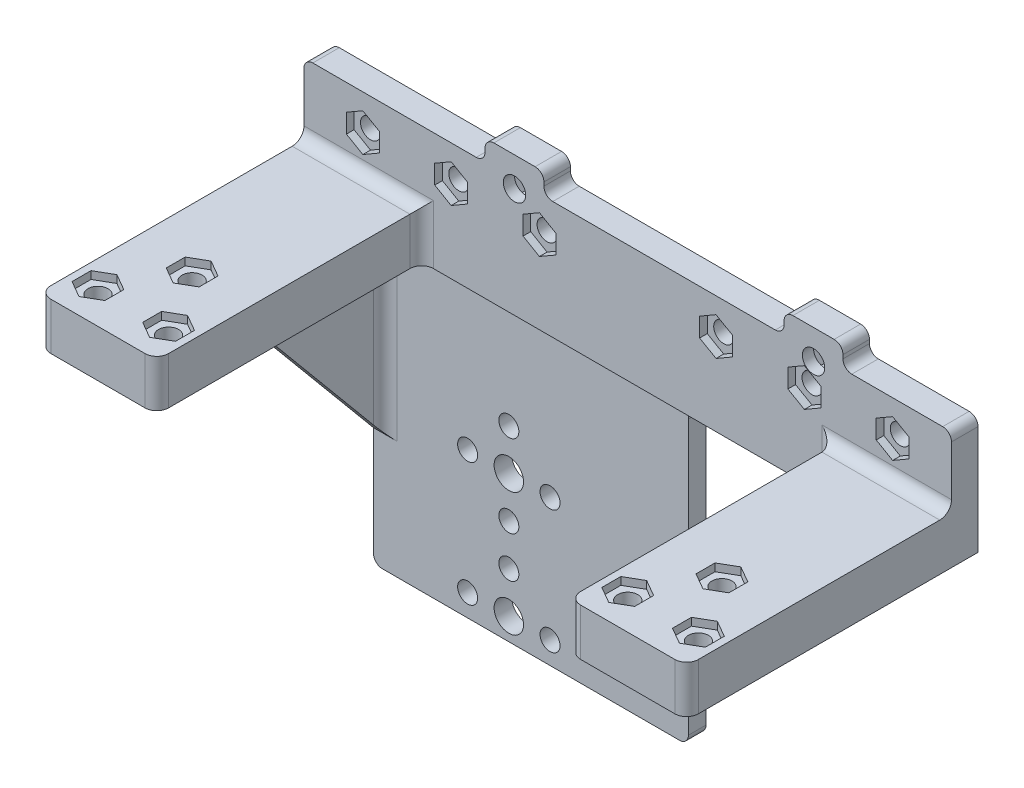
SolidWorks part; units mm, degrees
ref_plane "前视基准面" through (0, 0, 0) normal (0, 0, 1) x (1, 0, 0)
ref_plane "上视基准面" through (0, 0, 0) normal (0, 1, 0) x (1, 0, 0)
ref_plane "右视基准面" through (0, 0, 0) normal (1, 0, 0) x (0, 0, -1)
sketch "草图1" plane through (0, 0, 0) normal (0, 0, 1) x (1, 0, 0)
  line L6 (-55, 0) -> (55, 0)
  line L11 (55, 0) -> (55, 20)
  line L12 (55, 20) -> (-55, 20)
  line L13 (-55, 20) -> (-55, 0)
  line L14 (-45, 14) -> (45, 14) construction
  line L15 (0, 14) -> (0, 0) construction
  circle A6 centre (-45, 14) radius 1.7
  circle A7 centre (-30, 14) radius 1.7
  circle A8 centre (-15, 14) radius 1.7
  circle A9 centre (15, 14) radius 1.7
  circle A10 centre (30, 14) radius 1.7
  circle A11 centre (45, 14) radius 1.7
  dimension "D1" = 110
  dimension "D2" = 3.4
  dimension "D3" = 90
  dimension "D4" = 60
  dimension "D5" = 30
  dimension "D6" = 20
  dimension "D7" = 6
extrude "凸台-拉伸1" add sketch "草图1" along normal blind 4.5
sketch "草图2" plane through (0, 0, 4.5) normal (0, 0, 1) x (1, 0, 0)
  line L0 (0, 0) -> (0, 12.4325) construction
  line L1 (-55, 0) -> (-35, 0)
  line L2 (-55, 0) -> (-55, 8)
  line L3 (-55, 8) -> (-35, 8)
  line L4 (-35, 0) -> (-35, 8)
  line L5 (55, 0) -> (35, 0)
  line L6 (55, 0) -> (55, 8)
  line L7 (55, 8) -> (35, 8)
  line L8 (35, 0) -> (35, 8)
  dimension "D1" = 8
  dimension "D2" = 20
extrude "凸台-拉伸2" add sketch "草图2" along normal blind 45
sketch "草图3" plane through (0, 0, 4.5) normal (0, 0, 1) x (1, 0, 0)
  line L1 (-45, 17.22) -> (-47.7886, 15.61)
  line L2 (-47.7886, 15.61) -> (-47.7886, 12.39)
  line L3 (-47.7886, 12.39) -> (-45, 10.78)
  line L4 (-45, 10.78) -> (-42.2114, 12.39)
  line L5 (-42.2114, 12.39) -> (-42.2114, 15.61)
  line L6 (-42.2114, 15.61) -> (-45, 17.22)
  line L7 (-30, 17.22) -> (-32.7886, 15.61)
  line L8 (-32.7886, 15.61) -> (-32.7886, 12.39)
  line L9 (-32.7886, 12.39) -> (-30, 10.78)
  line L10 (-30, 10.78) -> (-27.2114, 12.39)
  line L11 (-27.2114, 12.39) -> (-27.2114, 15.61)
  line L12 (-27.2114, 15.61) -> (-30, 17.22)
  line L13 (-15, 17.22) -> (-17.7886, 15.61)
  line L14 (-17.7886, 15.61) -> (-17.7886, 12.39)
  line L15 (-17.7886, 12.39) -> (-15, 10.78)
  line L16 (-15, 10.78) -> (-12.2114, 12.39)
  line L17 (-12.2114, 12.39) -> (-12.2114, 15.61)
  line L18 (-12.2114, 15.61) -> (-15, 17.22)
  line L19 (15, 17.22) -> (12.2114, 15.61)
  line L20 (12.2114, 15.61) -> (12.2114, 12.39)
  line L21 (12.2114, 12.39) -> (15, 10.78)
  line L22 (15, 10.78) -> (17.7886, 12.39)
  line L23 (17.7886, 12.39) -> (17.7886, 15.61)
  line L24 (17.7886, 15.61) -> (15, 17.22)
  line L25 (30, 17.22) -> (27.2114, 15.61)
  line L26 (27.2114, 15.61) -> (27.2114, 12.39)
  line L27 (27.2114, 12.39) -> (30, 10.78)
  line L28 (30, 10.78) -> (32.7886, 12.39)
  line L29 (32.7886, 12.39) -> (32.7886, 15.61)
  line L30 (32.7886, 15.61) -> (30, 17.22)
  line L31 (45, 17.22) -> (42.2114, 15.61)
  line L32 (42.2114, 15.61) -> (42.2114, 12.39)
  line L33 (42.2114, 12.39) -> (45, 10.78)
  line L34 (45, 10.78) -> (47.7886, 12.39)
  line L35 (47.7886, 12.39) -> (47.7886, 15.61)
  line L36 (47.7886, 15.61) -> (45, 17.22)
  circle A0 centre (-45, 14) radius 2.7886 construction
  circle A1 centre (-30, 14) radius 2.7886 construction
  circle A2 centre (-15, 14) radius 2.7886 construction
  circle A3 centre (15, 14) radius 2.7886 construction
  circle A4 centre (30, 14) radius 2.7886 construction
  circle A5 centre (45, 14) radius 2.7886 construction
  dimension "D1" = 3.22
sketch "草图4" plane through (0, 0, 4.5) normal (0, 0, 1) x (1, 0, 0)
  line L1 (-24.2383, 13.6194) -> (-14.2383, 13.6194)
  line L2 (-24.2383, 13.6194) -> (-24.2383, 23.6194)
  line L3 (-24.2383, 23.6194) -> (-14.2383, 23.6194)
  line L4 (-14.2383, 13.6194) -> (-14.2383, 23.6194)
  line L5 (-24.2383, 13.6194) -> (-14.2383, 23.6194) construction
  line L6 (-24.2383, 23.6194) -> (-14.2383, 13.6194) construction
  line L7 (26.5617, 13.6194) -> (36.5617, 13.6194)
  line L8 (26.5617, 13.6194) -> (26.5617, 23.6194)
  line L9 (26.5617, 23.6194) -> (36.5617, 23.6194)
  line L10 (36.5617, 13.6194) -> (36.5617, 23.6194)
  line L11 (26.5617, 13.6194) -> (36.5617, 23.6194) construction
  line L12 (26.5617, 23.6194) -> (36.5617, 13.6194) construction
  point P0 (-19.2383, 18.6194)
  point P6 (31.5617, 18.6194)
  dimension "D1" = 10
extrude "凸台-拉伸3" add sketch "草图4" against normal up to surface (4.5 mm away) up to face at (0, 10, 0)
sketch "草图5" plane through (0, 0, 4.5) normal (0, 0, 1) x (1, 0, 0)
  circle A0 centre (-19.2383, 18.6194) radius 1.9
  circle A1 centre (31.5617, 18.6194) radius 1.9
  circle A2 centre (-15, 14) radius 1.7
  circle A3 centre (30, 14) radius 1.7
  dimension "D1" = 3.8
extrude "切除-拉伸1" cut sketch "草图5" against normal through all
extrude "切除-拉伸2" cut sketch "草图3" against normal blind 1.3
sketch "草图6" plane through (0, 0, 0) normal (0, 0, -1) x (-1, 0, 0)
  line L1 (-34.8617, 18.6194) -> (-33.2117, 15.7615)
  line L2 (-33.2117, 15.7615) -> (-29.9117, 15.7615)
  line L3 (-29.9117, 15.7615) -> (-28.2617, 18.6194)
  line L4 (-28.2617, 18.6194) -> (-29.9117, 21.4773)
  line L5 (-29.9117, 21.4773) -> (-33.2117, 21.4773)
  line L6 (-33.2117, 21.4773) -> (-34.8617, 18.6194)
  line L7 (15.9383, 18.6194) -> (17.5883, 15.7615)
  line L8 (17.5883, 15.7615) -> (20.8883, 15.7615)
  line L9 (20.8883, 15.7615) -> (22.5383, 18.6194)
  line L10 (22.5383, 18.6194) -> (20.8883, 21.4773)
  line L11 (20.8883, 21.4773) -> (17.5883, 21.4773)
  line L12 (17.5883, 21.4773) -> (15.9383, 18.6194)
  circle A0 centre (-31.5617, 18.6194) radius 2.8579 construction
  circle A1 centre (19.2383, 18.6194) radius 2.8579 construction
  dimension "D1" = 3.3
extrude "切除-拉伸3" cut sketch "草图6" against normal blind 2.6
sketch "草图7" plane through (0, 0, 0) normal (0, -1, 0) x (1, 0, 0)
  line L8 (-55, 0) -> (55, 0)
  line L9 (55, 0) -> (55, 49.5)
  line L10 (55, 49.5) -> (35, 49.5)
  line L11 (35, 49.5) -> (35, 4.5)
  line L12 (35, 4.5) -> (-35, 4.5)
  line L13 (-35, 4.5) -> (-35, 49.5)
  line L14 (-35, 49.5) -> (-55, 49.5)
  line L15 (-55, 49.5) -> (-55, 0)
  line L16 (-55, 0) -> (55, 0)
  line L17 (55, 0) -> (55, 49.5)
  line L18 (55, 49.5) -> (35, 49.5)
  line L19 (35, 49.5) -> (35, 4.5)
  line L20 (35, 4.5) -> (-35, 4.5)
  line L21 (-35, 4.5) -> (-35, 49.5)
  line L22 (-35, 49.5) -> (-55, 49.5)
  line L23 (-55, 49.5) -> (-55, 0)
  circle A0 centre (-51, 43.5) radius 1.7
  circle A1 centre (-39, 43.5) radius 1.7
  circle A2 centre (-45, 33.5) radius 1.7
  circle A3 centre (39, 43.5) radius 1.7
  circle A4 centre (51, 43.5) radius 1.7
  circle A5 centre (45, 33.5) radius 1.7
  dimension "D2" = 3.4
  dimension "D1" = 0
extrude "切除-拉伸5" cut sketch "草图7" against normal through all contours A0 | A1 | A2 | A4 | A3 | A5
sketch "草图8" plane through (0, 8, 0) normal (0, 1, 0) x (1, 0, 0)
  line L1 (51, -46.72) -> (53.7886, -45.11)
  line L2 (53.7886, -45.11) -> (53.7886, -41.89)
  line L3 (53.7886, -41.89) -> (51, -40.28)
  line L4 (51, -40.28) -> (48.2114, -41.89)
  line L5 (48.2114, -41.89) -> (48.2114, -45.11)
  line L6 (48.2114, -45.11) -> (51, -46.72)
  line L7 (39, -46.72) -> (41.7886, -45.11)
  line L8 (41.7886, -45.11) -> (41.7886, -41.89)
  line L9 (41.7886, -41.89) -> (39, -40.28)
  line L10 (39, -40.28) -> (36.2114, -41.89)
  line L11 (36.2114, -41.89) -> (36.2114, -45.11)
  line L12 (36.2114, -45.11) -> (39, -46.72)
  line L13 (45, -36.72) -> (47.7886, -35.11)
  line L14 (47.7886, -35.11) -> (47.7886, -31.89)
  line L15 (47.7886, -31.89) -> (45, -30.28)
  line L16 (45, -30.28) -> (42.2114, -31.89)
  line L17 (42.2114, -31.89) -> (42.2114, -35.11)
  line L18 (42.2114, -35.11) -> (45, -36.72)
  line L19 (-39, -46.72) -> (-36.2114, -45.11)
  line L20 (-36.2114, -45.11) -> (-36.2114, -41.89)
  line L21 (-36.2114, -41.89) -> (-39, -40.28)
  line L22 (-39, -40.28) -> (-41.7886, -41.89)
  line L23 (-41.7886, -41.89) -> (-41.7886, -45.11)
  line L24 (-41.7886, -45.11) -> (-39, -46.72)
  line L25 (-51, -46.72) -> (-48.2114, -45.11)
  line L26 (-48.2114, -45.11) -> (-48.2114, -41.89)
  line L27 (-48.2114, -41.89) -> (-51, -40.28)
  line L28 (-51, -40.28) -> (-53.7886, -41.89)
  line L29 (-53.7886, -41.89) -> (-53.7886, -45.11)
  line L30 (-53.7886, -45.11) -> (-51, -46.72)
  line L31 (-45, -36.72) -> (-42.2114, -35.11)
  line L32 (-42.2114, -35.11) -> (-42.2114, -31.89)
  line L33 (-42.2114, -31.89) -> (-45, -30.28)
  line L34 (-45, -30.28) -> (-47.7886, -31.89)
  line L35 (-47.7886, -31.89) -> (-47.7886, -35.11)
  line L36 (-47.7886, -35.11) -> (-45, -36.72)
  circle A0 centre (51, -43.5) radius 2.7886 construction
  circle A1 centre (39, -43.5) radius 2.7886 construction
  circle A2 centre (45, -33.5) radius 2.7886 construction
  circle A3 centre (-39, -43.5) radius 2.7886 construction
  circle A4 centre (-51, -43.5) radius 2.7886 construction
  circle A5 centre (-45, -33.5) radius 2.7886 construction
  dimension "D1" = 3.22
extrude "切除-拉伸6" cut sketch "草图8" against normal blind 1.3
sketch "草图9" plane through (0, 0, 0) normal (0, -1, 0) x (1, 0, 0)
  line L2 (-55, 0) -> (55, 0) construction
  line L3 (-55, 0) -> (55, 0)
  line L5 (-54, 3) -> (-54, 0)
  line L7 (26, 3) -> (26, 0)
  line L8 (0, 0) -> (0, 8.7602) construction
  line L9 (-54, 3) -> (26, 3)
  point P4 (26, 1.5)
  dimension "D1" = 80
  dimension "D2" = 3
  dimension "D3" = 54
extrude "凸台-拉伸4" add sketch "草图9" along normal blind 50 contours L9 L5 L3 L7 | L3 L8 L9 L5
sketch "草图11" plane through (0, 0, 0) normal (0, 0, -1) x (-1, 0, 0)
  line L0 (54, -50) -> (-26, -50) construction
  line L1 (54, -50) -> (-26, -50)
  line L2 (-26, -50) -> (-26, 0) construction
  line L3 (-26, -50) -> (-26, 0)
  line L4 (54, -50) -> (54, 0) construction
  line L5 (54, -50) -> (54, 0)
  line L6 (-8.8, -50) -> (-8.8, 0)
  line L7 (-8.8, 0) -> (-26, 0)
  line L8 (44.7, -50) -> (44.7, 0)
  line L9 (44.7, 0) -> (54, 0)
  line L10 (-26, 0) -> (-55, 0) construction
  line L11 (55, 0) -> (54, 0) construction
  line L22 (7.2, -64.75) -> (27.7, -64.75)
  line L23 (27.7, -64.75) -> (27.7, -56.75)
  line L24 (27.7, -56.75) -> (24.7, -56.75)
  line L25 (24.7, -56.75) -> (24.7, -54.75)
  line L26 (24.7, -54.75) -> (32.7, -54.75)
  line L27 (34.7, -52.75) -> (34.7, -18.75)
  line L28 (32.7, -16.75) -> (24.7, -16.75)
  line L29 (24.7, -16.75) -> (24.7, -14.75)
  line L30 (24.7, -14.75) -> (27.7, -14.75)
  line L31 (27.7, -14.75) -> (27.7, -6.75)
  line L32 (27.7, -6.75) -> (7.2, -6.75)
  line L33 (5.2, -8.75) -> (5.2, -14.75)
  line L34 (5.2, -14.75) -> (-0.8, -14.75)
  line L35 (-0.8, -14.75) -> (-0.8, -56.75)
  line L36 (-0.8, -56.75) -> (5.2, -56.75)
  line L37 (5.2, -56.75) -> (5.2, -62.75)
  line L38 (7.2, -64.75) -> (27.7, -64.75) construction
  line L39 (27.7, -64.75) -> (27.7, -56.75) construction
  line L40 (27.7, -56.75) -> (24.7, -56.75) construction
  line L41 (24.7, -56.75) -> (24.7, -54.75) construction
  line L42 (24.7, -54.75) -> (32.7, -54.75) construction
  line L43 (34.7, -52.75) -> (34.7, -18.75) construction
  line L44 (32.7, -16.75) -> (24.7, -16.75) construction
  line L45 (24.7, -16.75) -> (24.7, -14.75) construction
  line L46 (24.7, -14.75) -> (27.7, -14.75) construction
  line L47 (27.7, -14.75) -> (27.7, -6.75) construction
  line L48 (27.7, -6.75) -> (7.2, -6.75) construction
  line L49 (5.2, -8.75) -> (5.2, -14.75) construction
  line L50 (5.2, -14.75) -> (-0.8, -14.75) construction
  line L51 (-0.8, -14.75) -> (-0.8, -56.75) construction
  line L52 (-0.8, -56.75) -> (5.2, -56.75) construction
  line L53 (5.2, -56.75) -> (5.2, -62.75) construction
  circle A0 centre (21.7, -18.25) radius 1.7
  circle A1 centre (14.7, -25.25) radius 1.7
  circle A2 centre (21.7, -32.25) radius 1.7
  circle A3 centre (28.7, -25.25) radius 1.7
  arc A4 (32.7, -54.75) -> (34.7, -52.75) centre (32.7, -52.75) ccw
  arc A5 (34.7, -18.75) -> (32.7, -16.75) centre (32.7, -18.75) ccw
  arc A6 (7.2, -6.75) -> (5.2, -8.75) centre (7.2, -8.75) ccw
  arc A7 (5.2, -62.75) -> (7.2, -64.75) centre (7.2, -62.75) ccw
  arc A8 (32.7, -54.75) -> (34.7, -52.75) centre (32.7, -52.75) ccw construction
  arc A9 (34.7, -18.75) -> (32.7, -16.75) centre (32.7, -18.75) ccw construction
  arc A10 (7.2, -6.75) -> (5.2, -8.75) centre (7.2, -8.75) ccw construction
  arc A11 (5.2, -62.75) -> (7.2, -64.75) centre (7.2, -62.75) ccw construction
  circle A12 centre (21.7, -39.25) radius 1.7
  circle A13 centre (21.7, -46.25) radius 2.5
  circle A14 centre (21.7, -25.25) radius 2.5
  circle A15 centre (4.2, -35.75) radius 1.7
  circle A16 centre (28.7, -46.25) radius 1.7
  circle A17 centre (14.7, -46.25) radius 1.7
  circle A18 centre (21.7, -53.25) radius 1.7
  line M52 (-26, 0) -> (-26, -50)
  line M53 (-26, -50) -> (54, -50)
  line M54 (54, -50) -> (54, 0)
  dimension "D2" = 3.4
  dimension "D3" = 5
  dimension "D4" = 8
  dimension "D5" = 10
  dimension "D1" = 0
extrude "切除-拉伸7" cut sketch "草图11" against normal through all contours L6 L7 M52 M53 | L9 L8 M53 M54 | A13 | A17 | A16 | A12 | A2 | A1 | A0 | A3 | A14 | A15
sketch "草图12" plane through (-44.7, 0, 0) normal (-1, 0, 0) x (0, 0, 1)
  line L1 (3, -30) -> (28, 0)
  line L2 (3, 0) -> (3, -50) construction
  line L3 (49.5, 0) -> (0, 0) construction
  dimension "D1" = 25
  dimension "D2" = 30
rib "筋4" sketch "草图12" sketch "草图12" thickness 2 extrusion direction parallel to sketch draft on no parameters "D1"=2
fillet "圆角1" radius 2 8 edges at (-42.7, -15, 3) (-42.7, 0, 15.5) (35, 4, 4.5) (45, 8, 4.5) (-35, 4, 4.5) (-45, 8, 4.5) (8.8, 0, 1.5) (-44.7, 0, 14)
fillet "圆角2" radius 1.5 12 edges at (-55, 20, 2.25) (-24.2383, 20, 2.25) (-24.2383, 23.6194, 2.25) (-14.2383, 23.6194, 2.25) (-14.2383, 20, 2.25) (26.5617, 20, 2.25) (26.5617, 23.6194, 2.25) (36.5617, 23.6194, 2.25) (36.5617, 20, 2.25) (55, 20, 2.25) (8.8, -50, 1.5) (-44.7, -50, 1.5)
fillet "圆角3" radius 2 4 edges at (-55, 4, 49.5) (-35, 4, 49.5) (55, 4, 49.5) (35, 4, 49.5)
